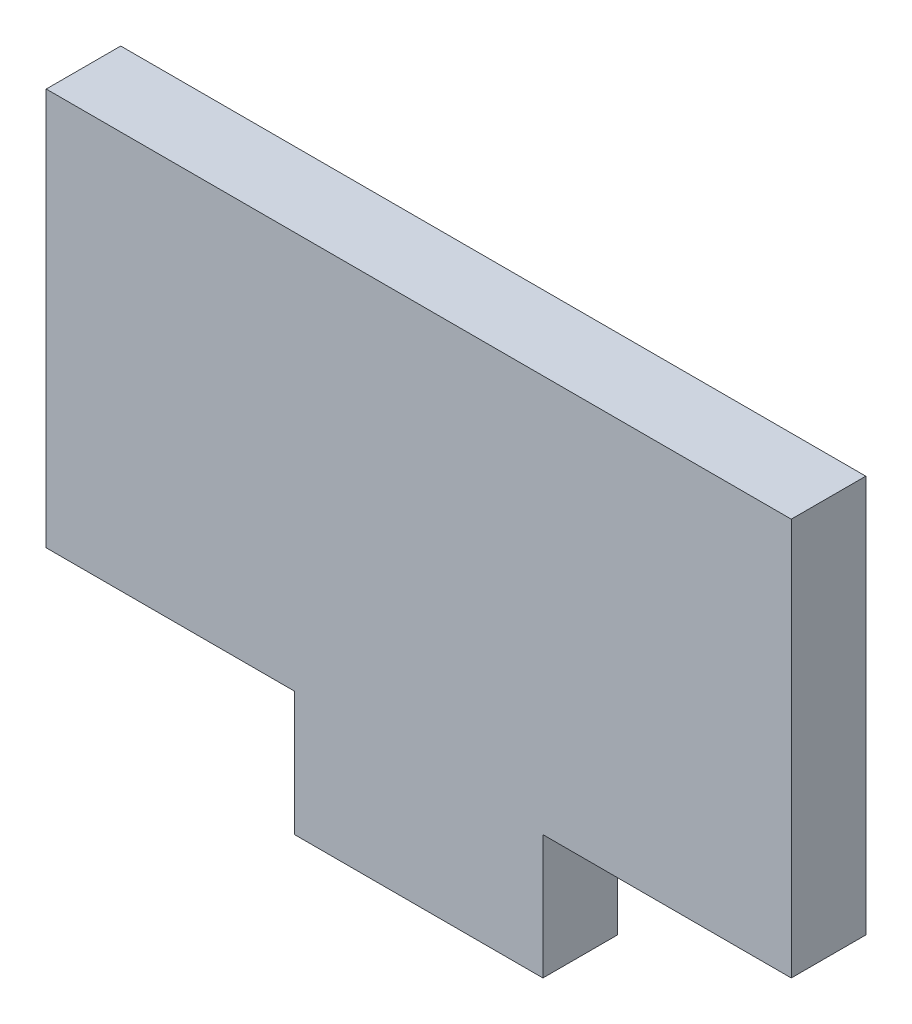
SolidWorks part; units mm, degrees
ref_plane "Front Plane" through (0, 0, 0) normal (0, 0, 1) x (1, 0, 0)
ref_plane "Top Plane" through (0, 0, 0) normal (0, 1, 0) x (1, 0, 0)
ref_plane "Right Plane" through (0, 0, 0) normal (1, 0, 0) x (0, 0, -1)
sketch "Sketch1" plane through (0, 0, 0) normal (0, 0, 1) x (1, 0, 0)
  line L1 (-15, 10.5) -> (15, 10.5)
  line L2 (-15, 10.5) -> (-15, -10.5)
  line L3 (-15, -10.5) -> (15, -10.5)
  line L4 (15, 10.5) -> (15, -10.5)
  line L5 (-15, 10.5) -> (15, -10.5) construction
  line L6 (-15, -10.5) -> (15, 10.5) construction
  point P0 (0, 0)
  dimension "D1" = 30
  dimension "D2" = 21
extrude "Boss-Extrude1" add sketch "Sketch1" along normal blind 3
sketch "Sketch3" plane through (0, 0, 3) normal (0, 0, 1) x (1, 0, 0)
  line L1 (-15, -10.5) -> (-5, -10.5)
  line L2 (-15, -10.5) -> (-15, -5.5)
  line L3 (-15, -5.5) -> (-5, -5.5)
  line L4 (-5, -10.5) -> (-5, -5.5)
  line L5 (15, -10.5) -> (5, -10.5)
  line L6 (15, -10.5) -> (15, -5.5)
  line L7 (15, -5.5) -> (5, -5.5)
  line L8 (5, -10.5) -> (5, -5.5)
  dimension "D1" = 5
  dimension "D2" = 5
  dimension "D3" = 10
  dimension "D4" = 10
extrude "Cut-Extrude1" cut sketch "Sketch3" against normal blind 3
